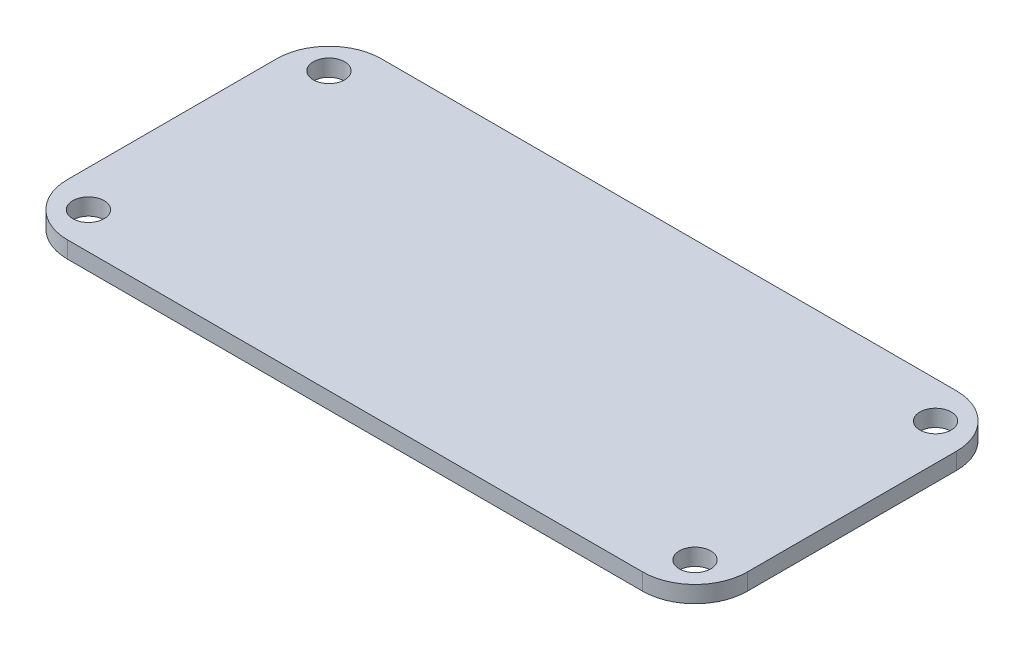
SolidWorks part; units mm, degrees
material "Alliage 2018"
ref_plane "Plan de face" through (0, 0, 0) normal (0, 0, 1) x (1, 0, 0)
ref_plane "Plan de dessus" through (0, 0, 0) normal (0, 1, 0) x (1, 0, 0)
ref_plane "Plan de droite" through (0, 0, 0) normal (1, 0, 0) x (0, 0, -1)
sketch "Esquisse1" plane through (0, 0, 0) normal (0, 1, 0) x (1, 0, 0)
  line L0 (0, 15) -> (0, 0) construction
  line L1 (-27.5, 15) -> (27.5, 15)
  line L2 (-32.5, 10) -> (-32.5, -10)
  line L3 (-27.5, -15) -> (27.5, -15)
  line L4 (32.5, 10) -> (32.5, -10)
  line L5 (-32.5, 15) -> (32.5, -15) construction
  line L6 (-32.5, -15) -> (32.5, 15) construction
  line L7 (0, 0) -> (-32.5, 0) construction
  circle A0 centre (-29, 11.5) radius 1.5
  circle A1 centre (29, 11.5) radius 1.5
  circle A2 centre (29, -11.5) radius 1.5
  circle A3 centre (-29, -11.5) radius 1.5
  arc A4 (27.5, -15) -> (32.5, -10) centre (27.5, -10) ccw
  arc A5 (-32.5, -10) -> (-27.5, -15) centre (-27.5, -10) ccw
  arc A6 (-27.5, 15) -> (-32.5, 10) centre (-27.5, 10) ccw
  arc A7 (27.5, 15) -> (32.5, 10) centre (27.5, 10) cw
  point P0 (0, 0)
  dimension "D3" = 3
  dimension "D6" = 5
  dimension "D7" = 5
  dimension "D1" = 65
  dimension "D2" = 30
  dimension "D4" = 3.5
  dimension "D5" = 3.5
extrude "Boss.-Extru.1" add sketch "Esquisse1" along normal blind 1.6
